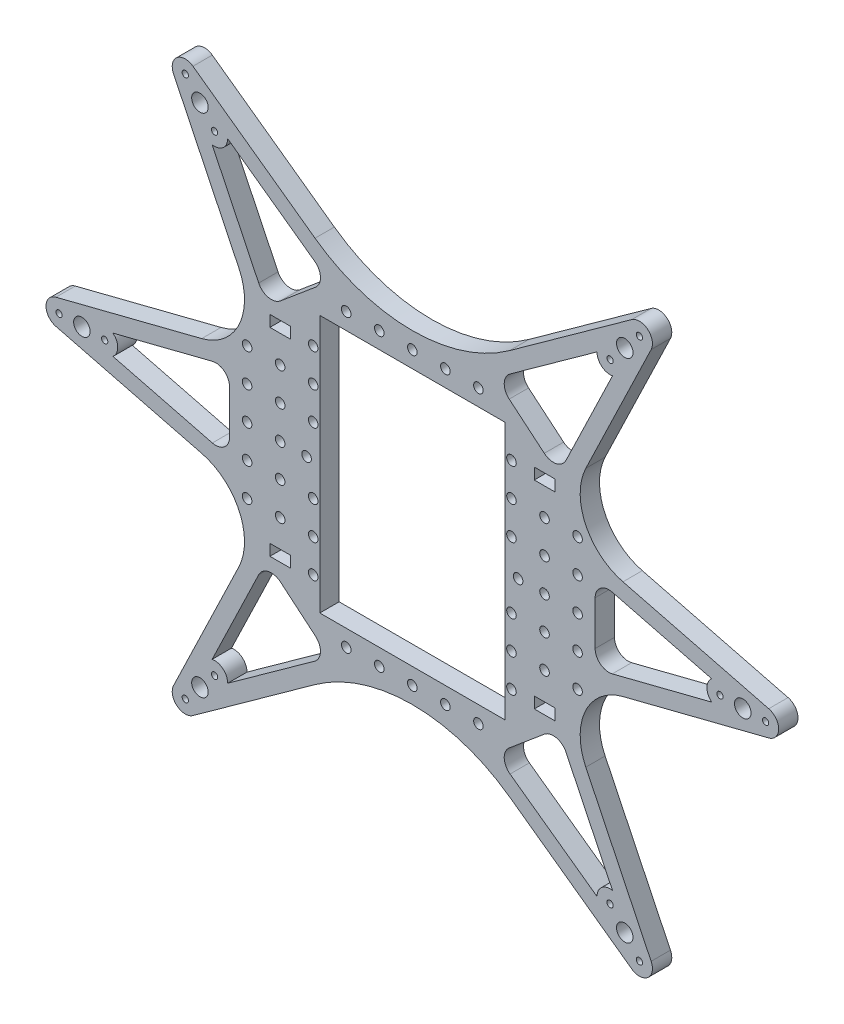
SolidWorks part; units mm, degrees
material "Acrylic (Medium-high impact)"
ref_plane "Front Plane" through (0, 0, 0) normal (0, 0, 1) x (1, 0, 0)
ref_plane "Top Plane" through (0, 0, 0) normal (0, 1, 0) x (1, 0, 0)
ref_plane "Right Plane" through (0, 0, 0) normal (1, 0, 0) x (0, 0, -1)
sketch "Sketch1" plane through (0, 0, 0) normal (0, 0, 1) x (1, 0, 0)
  line L0 (587.7828, 489.7111) -> (587.7828, 411.3893) construction
  line L1 (549.677, 453.6081) -> (579.7591, 461.2509)
  line L2 (603.3767, 418.8502) -> (597.1767, 422.2502) construction
  line L3 (600.2767, 420.5502) -> (600.2767, 429.1002) construction
  line L4 (600.2767, 429.1002) -> (600.2767, 420.5502) construction
  line L5 (603.3767, 422.2502) -> (597.1767, 418.8502) construction
  line L6 (532.4267, 446.7161) -> (532.4267, 450.5502) construction
  line L7 (576.5352, 435.5097) -> (532.4267, 446.7161)
  line L8 (635.8061, 455.8779) -> (-31503.5744, 38758.1001) construction
  line L9 (532.4267, 450.5502) -> (532.4267, 454.3842) construction
  line L10 (603.3767, 422.2502) -> (603.3767, 418.8502)
  line L11 (603.3767, 422.2502) -> (597.1767, 422.2502)
  line L12 (597.1767, 422.2502) -> (597.1767, 418.8502)
  line L13 (549.677, 447.4923) -> (579.7591, 439.8495)
  line L14 (575.9979, 527.1546) -> (571.5627, 532.4403) construction
  line L15 (575.9979, 527.1546) -> (580.4331, 521.8689) construction
  line L16 (603.3767, 418.8502) -> (597.1767, 418.8502)
  line L17 (576.5352, 465.5907) -> (576.5352, 435.5097) construction
  line L18 (668.2767, 450.5502) -> (612.2767, 450.5502) construction
  line L19 (570.952, 533.1681) -> (573.8891, 535.6326) construction
  line L20 (-358.0106, 401.5502) -> (49641.9894, 401.5502) construction
  line L21 (540.2767, 450.5502) -> (547.1767, 450.5502) construction
  line L22 (-350.6447, 450.5502) -> (49649.3553, 450.5502) construction
  line L23 (680.2767, 472.0002) -> (680.2767, 429.1002) construction
  line L24 (584.9585, 457.2073) -> (584.9585, 443.8931)
  line L25 (683.3767, 482.2502) -> (677.1767, 478.8502) construction
  line L26 (587.7828, 489.7111) -> (568.0149, 530.7036)
  line L27 (680.2767, 480.5502) -> (680.2767, 470.5502) construction
  line L28 (680.2767, 470.5502) -> (680.2767, 480.5502) construction
  line L29 (683.3767, 478.8502) -> (677.1767, 482.2502) construction
  line L30 (610.8261, 509.0468) -> (573.8891, 535.6326)
  line L31 (568.0149, 530.7036) -> (570.952, 533.1681) construction
  line L32 (610.2922, 450.5502) -> (612.2767, 450.5502) construction
  line L33 (612.2767, 489.5502) -> (668.2767, 489.5502)
  line L34 (663.7936, 478.5766) -> (-31475.5869, -37823.6456) construction
  line L35 (540.2767, 450.5502) -> (533.3767, 450.5502) construction
  line L36 (576.5352, 465.5907) -> (532.4267, 454.3842)
  line L37 (575.9979, 373.9457) -> (571.5627, 368.66) construction
  line L38 (600.3483, 413.737) -> (610.9562, 404.8359)
  line L39 (709.6013, 367.9323) -> (712.5384, 370.3968) construction
  line L40 (579.6978, 383.1124) -> (593.7859, 412.3268)
  line L41 (640.2767, 450.5502) -> (668.2767, 450.5502) construction
  line L42 (706.6642, 365.4678) -> (709.6013, 367.9323) construction
  line L43 (704.5554, 373.9457) -> (700.1202, 379.2314) construction
  line L44 (704.5554, 373.9457) -> (708.9906, 368.66) construction
  line L45 (740.2767, 450.5502) -> (747.1767, 450.5502) construction
  line L46 (584.3828, 379.1812) -> (610.707, 398.1283)
  line L47 (670.2611, 450.5502) -> (668.2767, 450.5502) construction
  line L48 (575.9979, 373.9457) -> (580.4331, 379.2314) construction
  line L49 (587.7828, 411.3893) -> (568.0149, 370.3968)
  line L50 (712.5384, 530.7036) -> (709.6013, 533.1681) construction
  line L51 (740.2767, 450.5502) -> (733.3767, 450.5502) construction
  line L52 (573.8891, 365.4678) -> (570.952, 367.9323) construction
  line L53 (570.952, 367.9323) -> (568.0149, 370.3968) construction
  line L54 (709.6013, 533.1681) -> (706.6642, 535.6326) construction
  line L55 (610.8261, 392.0536) -> (573.8891, 365.4678)
  line L56 (704.0181, 465.5907) -> (704.0181, 435.5097) construction
  line L57 (640.2767, 406.5502) -> (640.2767, 411.5502) construction
  line L58 (704.5554, 527.1546) -> (700.1202, 521.8689) construction
  line L59 (704.5554, 527.1546) -> (708.9906, 532.4403) construction
  line L60 (748.1267, 450.5502) -> (748.1267, 454.3842) construction
  line L61 (748.1267, 446.7161) -> (748.1267, 450.5502) construction
  line L62 (1631.1668, 450.5502) -> (-48368.8332, 450.5502) construction
  line L63 (691.1714, 450.5502) -> (589.3819, 450.5502) construction
  line L64 (677.1767, 422.2502) -> (683.3767, 418.8502) construction
  line L65 (680.2767, 429.1002) -> (680.2767, 420.5502) construction
  line L66 (680.2767, 420.5502) -> (680.2767, 429.1002) construction
  line L67 (692.7705, 489.7111) -> (692.7705, 411.3893) construction
  line L68 (-358.194, 499.5502) -> (49641.806, 499.5502) construction
  line L69 (579.6978, 517.988) -> (593.7859, 488.7736)
  line L70 (677.1767, 418.8502) -> (683.3767, 422.2502) construction
  line L71 (683.3767, 478.8502) -> (683.3767, 482.2502)
  line L72 (612.2767, 489.5502) -> (612.2767, 411.5502)
  line L73 (584.3828, 521.9191) -> (610.707, 502.9721)
  line L74 (610.9562, 496.2644) -> (600.3483, 487.3634)
  line L75 (683.3767, 478.8502) -> (677.1767, 478.8502)
  line L76 (677.1767, 478.8502) -> (677.1767, 482.2502)
  line L77 (669.5971, 496.2644) -> (680.205, 487.3634)
  line L78 (696.1705, 521.9191) -> (669.8463, 502.9721)
  line L79 (668.2767, 489.5502) -> (668.2767, 411.5502)
  line L80 (612.2767, 411.5502) -> (668.2767, 411.5502)
  line L81 (700.8555, 517.988) -> (686.7674, 488.7736)
  line L82 (669.7272, 392.0536) -> (706.6642, 365.4678)
  line L83 (692.7705, 411.3893) -> (712.5384, 370.3968)
  line L84 (696.1705, 379.1812) -> (669.8463, 398.1283)
  line L85 (700.8555, 383.1124) -> (686.7674, 412.3268)
  line L86 (680.205, 413.737) -> (669.5971, 404.8359)
  line L87 (704.0181, 465.5907) -> (748.1267, 454.3842)
  line L88 (669.7272, 509.0468) -> (706.6642, 535.6326)
  line L89 (692.7705, 489.7111) -> (712.5384, 530.7036)
  line L90 (695.5948, 457.2073) -> (695.5948, 443.8931)
  line L91 (683.3767, 482.2502) -> (677.1767, 482.2502)
  line L92 (730.8763, 447.4923) -> (700.7942, 439.8495)
  line L93 (677.1767, 418.8502) -> (683.3767, 418.8502)
  line L94 (683.3767, 422.2502) -> (683.3767, 418.8502)
  line L95 (677.1767, 422.2502) -> (683.3767, 422.2502)
  line L96 (704.0181, 435.5097) -> (748.1267, 446.7161)
  line L97 (730.8763, 453.6081) -> (700.7942, 461.2509)
  line L98 (677.1767, 422.2502) -> (677.1767, 418.8502)
  line L99 (610.2767, 480.5502) -> (610.2767, 470.5502) construction
  line L100 (590.2767, 450.5502) -> (590.2767, 460.5502) construction
  line L101 (600.2767, 470.5502) -> (600.2767, 460.5502) construction
  line L102 (640.2767, 494.5502) -> (630.2767, 494.5502) construction
  line L103 (640.2767, 406.5502) -> (630.2767, 406.5502) construction
  line L104 (569.4061, 521.6235) -> (581.9819, 532.1758) construction
  line L111 (640.2767, -499.8656) -> (640.2767, 49500.1344) construction
  line L157 (597.1767, 482.2502) -> (603.3767, 482.2502)
  line L158 (603.3767, 478.8502) -> (603.3767, 482.2502)
  line L159 (597.1767, 478.8502) -> (603.3767, 482.2502) construction
  line L160 (600.2767, 470.5502) -> (600.2767, 480.5502) construction
  line L161 (600.2767, 480.5502) -> (600.2767, 470.5502) construction
  line L162 (597.1767, 482.2502) -> (603.3767, 478.8502) construction
  line L163 (597.1767, 478.8502) -> (603.3767, 478.8502)
  line L164 (597.1767, 478.8502) -> (597.1767, 482.2502)
  line L165 (600.2767, 472.0002) -> (600.2767, 429.1002) construction
  circle A0 centre (533.3767, 450.5502) radius 0.95
  arc A1 (584.9585, 443.8931) -> (579.7591, 439.8495) centre (580.7864, 443.8931) cw
  circle A2 centre (575.9979, 527.1546) radius 2.5
  circle A3 centre (547.1767, 450.5502) radius 0.95
  arc A4 (549.677, 447.4923) -> (549.677, 453.6081) centre (547.1767, 450.5502) ccw
  circle A5 centre (540.2767, 450.5502) radius 2.5
  arc A6 (532.4267, 446.7161) -> (532.4267, 454.3842) centre (533.3767, 450.5502) cw
  circle A7 centre (590.2767, 460.5502) radius 1.45
  circle A8 centre (571.5627, 532.4403) radius 0.95
  circle A9 centre (580.4331, 521.8689) radius 0.95
  arc A10 (579.6978, 517.988) -> (584.3828, 521.9191) centre (580.4331, 521.8689) ccw
  arc A11 (584.9585, 457.2073) -> (579.7591, 461.2509) centre (580.7864, 457.2073) ccw
  arc A12 (610.9562, 404.8359) -> (610.707, 398.1283) centre (608.2233, 401.579) cw
  circle A13 centre (680.2767, 470.5502) radius 1.45
  arc A14 (584.3828, 379.1812) -> (579.6978, 383.1124) centre (580.4331, 379.2314) ccw
  arc A15 (568.0149, 530.7036) -> (573.8891, 535.6326) centre (571.5627, 532.4403) cw
  circle A16 centre (610.2767, 480.5502) radius 1.45
  circle A17 centre (610.2767, 470.5502) radius 1.45
  circle A18 centre (610.2767, 460.5502) radius 1.45
  circle A19 centre (608.2767, 450.5502) radius 1.45
  circle A20 centre (630.2767, 494.5502) radius 1.45
  circle A21 centre (620.2767, 494.5502) radius 1.45
  circle A22 centre (640.2767, 406.5502) radius 1.45
  circle A23 centre (630.2767, 406.5502) radius 1.45
  circle A24 centre (620.2767, 406.5502) radius 1.45
  circle A25 centre (670.2767, 420.5502) radius 1.45
  arc A26 (600.3483, 413.737) -> (593.7859, 412.3268) centre (597.6155, 410.4801) ccw
  circle A27 centre (580.4331, 379.2314) radius 0.95
  circle A28 centre (575.9979, 373.9457) radius 2.5
  circle A29 centre (571.5627, 368.66) radius 0.95
  arc A30 (573.8891, 365.4678) -> (568.0149, 370.3968) centre (571.5627, 368.66) cw
  arc A31 (610.8261, 509.0468) -> (669.7272, 509.0468) centre (640.2767, 549.964) ccw
  arc A34 (610.8261, 392.0536) -> (669.7272, 392.0536) centre (640.2767, 351.1364) cw
  arc A35 (576.5352, 435.5097) -> (587.7828, 411.3893) centre (572.3036, 418.8538) cw
  arc A36 (600.3483, 487.3634) -> (593.7859, 488.7736) centre (597.6155, 490.6203) cw
  arc A37 (610.9562, 496.2644) -> (610.707, 502.9721) centre (608.2233, 499.5213) ccw
  arc A38 (576.5352, 465.5907) -> (587.7828, 489.7111) centre (572.3036, 482.2466) ccw
  circle A39 centre (610.2767, 450.5502) radius 1.45 [skipped]
  circle A40 centre (590.2767, 430.5502) radius 1.45
  circle A41 centre (670.2767, 430.5502) radius 1.45
  circle A42 centre (590.2767, 440.5502) radius 1.45
  circle A43 centre (670.2767, 440.5502) radius 1.45
  arc A44 (704.0181, 465.5907) -> (692.7705, 489.7111) centre (708.2497, 482.2466) cw
  arc A45 (669.5971, 496.2644) -> (669.8463, 502.9721) centre (672.33, 499.5213) cw
  arc A46 (680.205, 487.3634) -> (686.7674, 488.7736) centre (682.9378, 490.6203) ccw
  arc A47 (704.0181, 435.5097) -> (692.7705, 411.3893) centre (708.2497, 418.8538) ccw
  circle A48 centre (610.2767, 440.5502) radius 1.45
  circle A49 centre (590.2767, 470.5502) radius 1.45
  circle A50 centre (680.2767, 430.5502) radius 1.45
  arc A51 (706.6642, 365.4678) -> (712.5384, 370.3968) centre (708.9906, 368.66) ccw
  circle A52 centre (708.9906, 368.66) radius 0.95
  circle A53 centre (704.5554, 373.9457) radius 2.5
  circle A54 centre (700.1202, 379.2314) radius 0.95
  arc A55 (680.205, 413.737) -> (686.7674, 412.3268) centre (682.9378, 410.4801) cw
  circle A56 centre (660.2767, 406.5502) radius 1.45
  circle A57 centre (650.2767, 406.5502) radius 1.45
  circle A58 centre (660.2767, 494.5502) radius 1.45
  circle A59 centre (650.2767, 494.5502) radius 1.45
  circle A60 centre (672.2767, 450.5502) radius 1.45
  circle A61 centre (670.2767, 460.5502) radius 1.45
  circle A62 centre (670.2767, 470.5502) radius 1.45
  arc A63 (712.5384, 530.7036) -> (706.6642, 535.6326) centre (708.9906, 532.4403) ccw
  arc A64 (696.1705, 379.1812) -> (700.8555, 383.1124) centre (700.1202, 379.2314) cw
  arc A65 (669.5971, 404.8359) -> (669.8463, 398.1283) centre (672.33, 401.579) ccw
  arc A66 (695.5948, 457.2073) -> (700.7942, 461.2509) centre (699.7669, 457.2073) cw
  arc A67 (700.8555, 517.988) -> (696.1705, 521.9191) centre (700.1202, 521.8689) cw
  circle A68 centre (700.1202, 521.8689) radius 0.95
  circle A69 centre (708.9906, 532.4403) radius 0.95
  circle A70 centre (690.2767, 450.5502) radius 1.45
  arc A71 (748.1267, 446.7161) -> (748.1267, 454.3842) centre (747.1767, 450.5502) ccw
  circle A72 centre (740.2767, 450.5502) radius 2.5
  circle A73 centre (610.2767, 430.5502) radius 1.45
  arc A74 (730.8763, 447.4923) -> (730.8763, 453.6081) centre (733.3767, 450.5502) cw
  circle A75 centre (733.3767, 450.5502) radius 0.95
  circle A76 centre (704.5554, 527.1546) radius 2.5
  arc A77 (695.5948, 443.8931) -> (700.7942, 439.8495) centre (699.7669, 443.8931) ccw
  circle A78 centre (747.1767, 450.5502) radius 0.95
  circle A79 centre (610.2767, 420.5502) radius 1.45
  circle A80 centre (670.2767, 480.5502) radius 1.45
  circle A81 centre (690.2767, 470.5502) radius 1.45
  circle A82 centre (640.2767, 494.5502) radius 1.45
  circle A83 centre (690.2767, 440.5502) radius 1.45
  circle A84 centre (690.2767, 430.5502) radius 1.45
  circle A86 centre (690.2767, 460.5502) radius 1.45
  circle A88 centre (600.2767, 460.5502) radius 1.45
  circle A89 centre (590.2767, 450.5502) radius 1.45
  circle A90 centre (600.2767, 450.5502) radius 1.45
  circle A91 centre (600.2767, 440.5502) radius 1.45
  circle A92 centre (600.2767, 430.5502) radius 1.45
  circle A93 centre (680.2767, 440.5502) radius 1.45
  circle A96 centre (680.2767, 450.5502) radius 1.45
  circle A97 centre (680.2767, 460.5502) radius 1.45
  circle A129 centre (600.2767, 470.5502) radius 1.45
  circle A130 centre (590.2767, 480.5502) radius 1.45 [skipped]
  point P0 (640.2767, 499.5502)
  point P1 (640.2767, 401.5502)
  point P25 (600.2767, 420.5502)
  point P39 (600.2767, 450.5502)
  point P46 (584.9585, 450.5502)
  point P54 (605.6523, 491.8139)
  point P64 (584.9585, 450.5502)
  point P88 (605.6523, 409.2865)
  point P92 (605.6523, 409.2865)
  point P104 (640.2767, 489.5502)
  point P124 (605.6523, 491.8139)
  point P229 (674.901, 491.8139)
  point P230 (674.901, 409.2865)
  point P231 (695.5948, 450.5502)
  point P238 (640.2767, 489.5502)
  point P240 (612.2767, 450.5502)
  point P242 (569.0236, 535.4662)
  point P307 (640.2767, 499.5502)
  point P366 (600.2767, 480.5502)
  dimension "D6" = 1.9
  dimension "D9" = 30
  dimension "D7" = 30
  dimension "D11" = 5
  dimension "D12" = 13.8
  dimension "D5" = 50
  dimension "D14" = 5
  dimension "D15" = 50
  dimension "D16" = 4
  dimension "D17" = 3
  dimension "D18" = 3
  dimension "D19" = 75
  dimension "D20" = 2.9
  dimension "D13" = 56
  dimension "D27" = 5
  dimension "D8" = 1.9
  dimension "D36" = 3
  dimension "D37" = 3
  dimension "D29" = 1.9
  dimension "D47" = 5
  dimension "D28" = 3
  dimension "D25" = 3
  dimension "D38" = 3
  dimension "D39" = 3
  dimension "D48" = 2.9
  dimension "D26" = 32
  dimension "D52" = 5
  dimension "D10" = 10
  dimension "D21" = 5
  dimension "D22" = 13.8
  dimension "D23" = 78
  dimension "D24" = 5
  dimension "D30" = 13.8
  dimension "D31" = 75
  dimension "D32" = 98
  dimension "D33" = 50
  dimension "D34" = 6.2
  dimension "D35" = 100
  dimension "D40" = 100
  dimension "D41" = 5
  dimension "D42" = 5
  dimension "D43" = 100
  dimension "D44" = 3.4
  dimension "D45" = 40
  dimension "D46" = 30
  dimension "D49" = 30
  dimension "D51" = 10
  dimension "D53" = 10
  dimension "D54" = 10
  dimension "D55" = 10
  dimension "D56" = 10
  dimension "D57" = 10
  dimension "D58" = 10
  dimension "D59" = 5
  dimension "D50" = 7
extrude "Boss-Extrude1" add sketch "Sketch1" along normal blind 5.85
